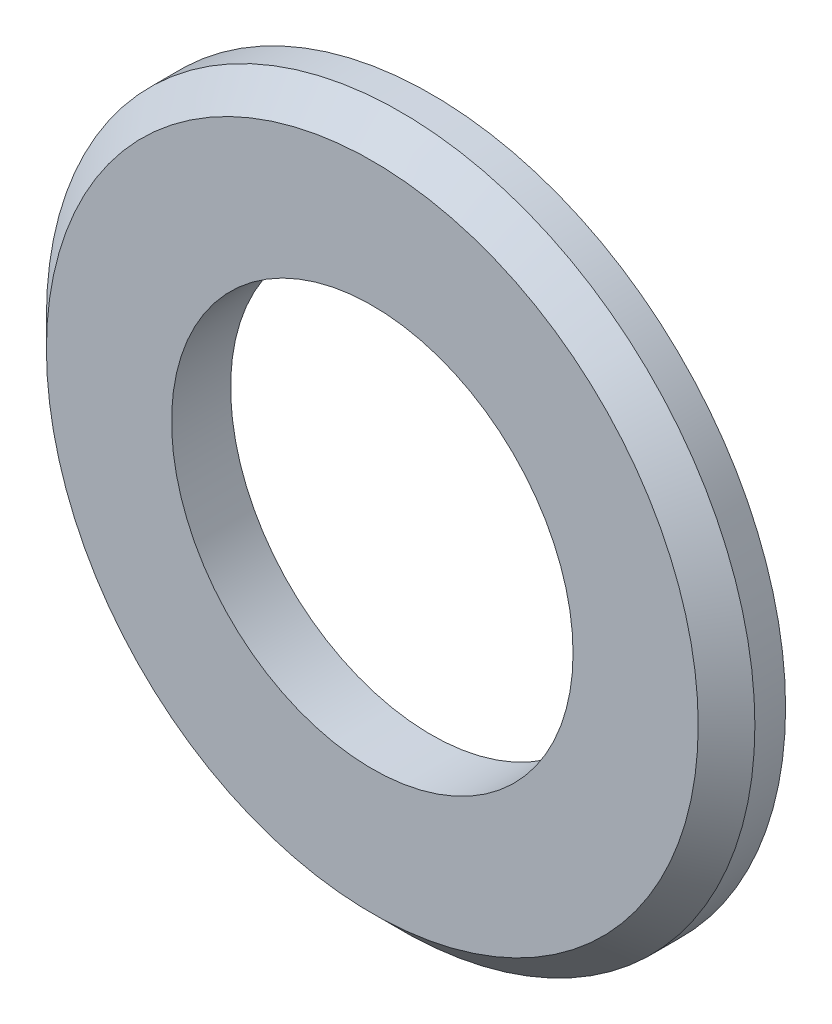
SolidWorks part; units mm, degrees
ref_plane "Спереди" through (0, 0, 0) normal (0, 0, 1) x (1, 0, 0)
ref_plane "Сверху" through (0, 0, 0) normal (0, 1, 0) x (1, 0, 0)
ref_plane "Справа" through (0, 0, 0) normal (1, 0, 0) x (0, 0, -1)
other "Configuration Table"
sketch "Эскиз1" plane through (0, 0, 0) normal (0, 0, 1) x (1, 0, 0)
  circle A0 centre (0, 0) radius 8.5
  circle A1 centre (0, 0) radius 15
  dimension "D1" = 8.5
  dimension "D2" = 15
extrude "Бобышка-Вытянуть1" add sketch "Эскиз1" along normal blind 2.5
chamfer "Фаска1" distance 1.2 angle 45 1 edges at (15, 0, 2.5)
